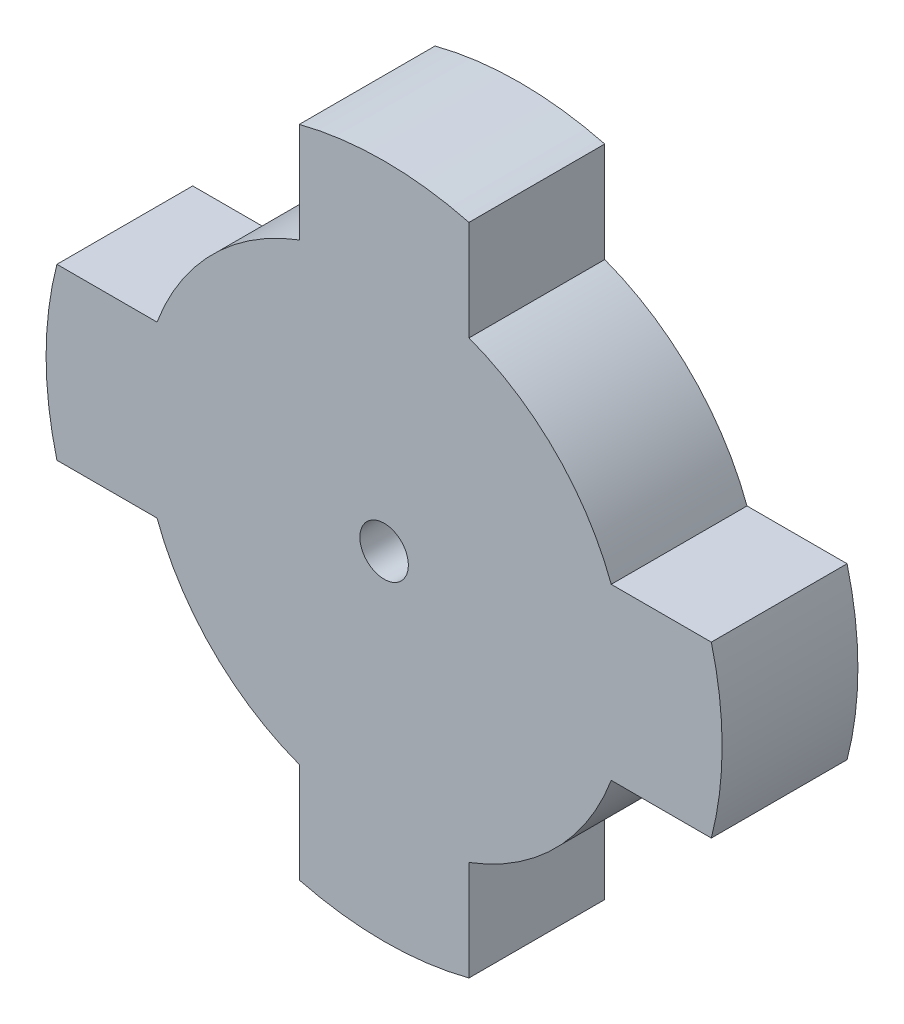
SolidWorks part; units mm, degrees
ref_plane "Front Plane" through (0, 0, 0) normal (0, 0, 1) x (1, 0, 0)
ref_plane "Top Plane" through (0, 0, 0) normal (0, 1, 0) x (1, 0, 0)
ref_plane "Right Plane" through (0, 0, 0) normal (1, 0, 0) x (0, 0, -1)
sketch "Rotor_Sketch" plane through (0, 0, 0) normal (0, 0, 1) x (1, 0, 0)
  line L0 (0, 0) -> (0, 25) construction
  line L2 (-8.75, 33.7378) -> (-8.75, 23.4187)
  line L3 (8.75, 33.7378) -> (8.75, 23.4187)
  line L4 (33.7378, 8.75) -> (23.4187, 8.75)
  line L6 (33.7378, -8.75) -> (23.4187, -8.75)
  line L7 (8.75, -33.7378) -> (8.75, -23.4187)
  line L9 (-8.75, -33.7378) -> (-8.75, -23.4187)
  line L10 (-33.7378, -8.75) -> (-23.4187, -8.75)
  line L12 (-33.7378, 8.75) -> (-23.4187, 8.75)
  line L13 (0, 35.565) -> (0, 37.7737) construction
  arc A4 (-8.75, 23.4187) -> (-23.4187, 8.75) centre (0, 0) ccw
  circle A5 centre (0, 0) radius 2.5
  arc A6 (23.4187, 8.75) -> (8.75, 23.4187) centre (0, 0) ccw
  arc A7 (8.75, -23.4187) -> (23.4187, -8.75) centre (0, 0) ccw
  arc A8 (-23.4187, -8.75) -> (-8.75, -23.4187) centre (0, 0) ccw
  arc A11 (-8.75, -33.7378) -> (8.75, -33.7378) centre (0, 0) ccw
  arc A12 (33.7378, -8.75) -> (33.7378, 8.75) centre (0, 0) ccw
  arc A13 (8.75, 33.7378) -> (-8.75, 33.7378) centre (0, 0) ccw
  arc A14 (-33.7378, 8.75) -> (-33.7378, -8.75) centre (0, 0) ccw
  point P8 (0, 35.565)
  point P23 (0, 0)
  dimension "D1" = 50
  dimension "D4" = 5
  dimension "D3" = 4
extrude "Rotor" add sketch "Rotor_Sketch" along normal blind 14
